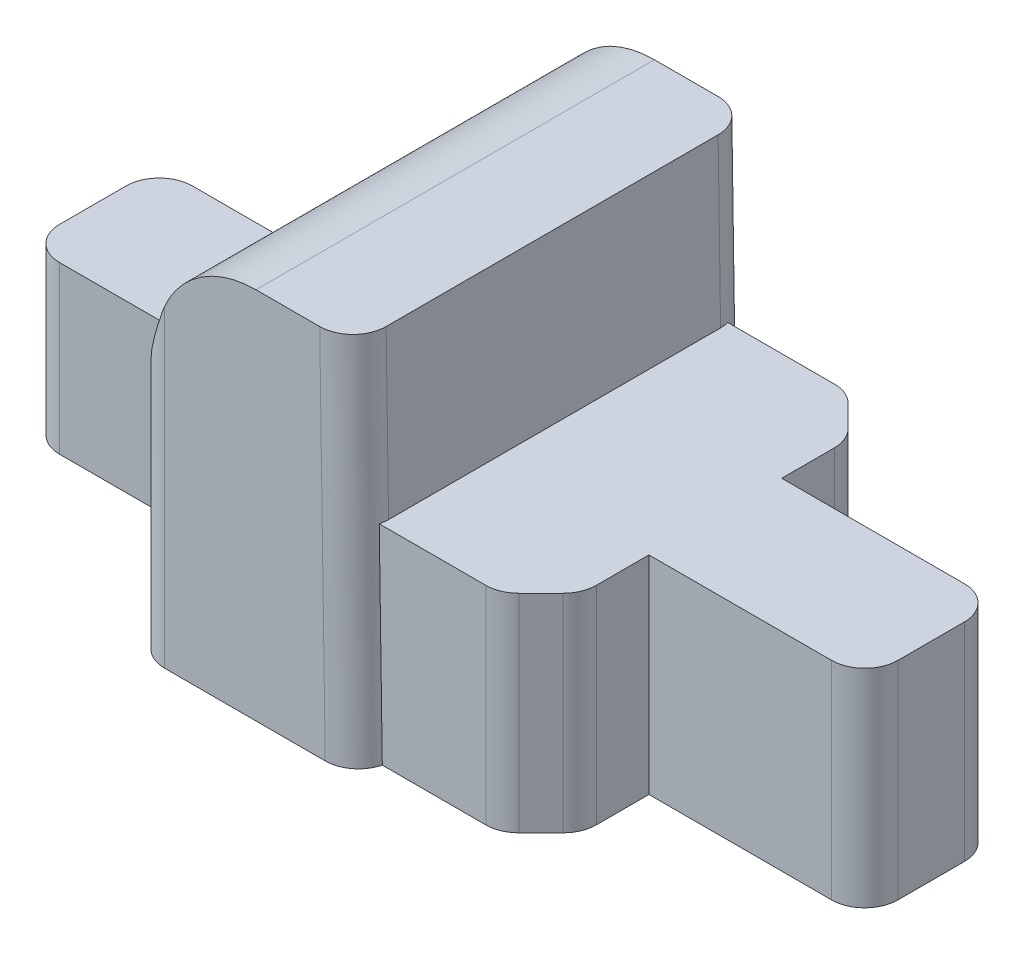
SolidWorks part; units mm, degrees
ref_plane "Front Plane" through (0, 0, 0) normal (0, 0, 1) x (1, 0, 0)
ref_plane "Top Plane" through (0, 0, 0) normal (0, 1, 0) x (1, 0, 0)
ref_plane "Right Plane" through (0, 0, 0) normal (1, 0, 0) x (0, 0, -1)
ref_plane "Plane1" through (0, 0, 203.2) normal (0, 0, 1) x (1, 0, 0)
sketch "Sketch2" plane through (0, 0, 203.2) normal (0, 0, 1) x (1, 0, 0)
  line L0 (0, 0) -> (-660.4, 0)
  line L1 (-660.4, 0) -> (-660.4, 508)
  line L2 (-660.4, 508) -> (0, 508)
  line L3 (0, 508) -> (0, 0)
  dimension "D1" = 660.4
  dimension "D2" = 508
ref_plane "Plane2" through (0, 0, 609.6) normal (0, 0, 1) x (1, 0, 0)
sketch "Sketch3" plane through (0, 0, 609.6) normal (0, 0, 1) x (1, 0, 0)
  line L1 (0, 0) -> (0, 508)
  line L2 (0, 0) -> (762, 0)
  line L3 (762, 0) -> (745.0612, 1143)
  line L4 (237.0612, 1143) -> (745.0612, 1143)
  line L5 (0, 508) -> (237.0612, 1143)
  dimension "D1" = 762
  dimension "D2" = 1143
  dimension "D3" = 508
ref_plane "Plane3" through (0, 0, 533.4) normal (0, 0, 1) x (1, 0, 0)
sketch "Sketch4" plane through (0, 0, 533.4) normal (0, 0, 1) x (1, 0, 0)
  line L1 (1244.6, 635) -> (752.5896, 635)
  line L2 (762, 0) -> (1244.6, 0)
  line L3 (1244.6, 0) -> (1244.6, 635)
  line L4 (762, 0) -> (745.0612, 1143) construction
  line L5 (752.5896, 635) -> (762, 0)
  dimension "D1" = 482.6
  dimension "D2" = 635
ref_plane "Plane4" through (0, 0, 203.2) normal (0, 0, 1) x (1, 0, 0)
sketch "Sketch5" plane through (0, 0, 203.2) normal (0, 0, 1) x (1, 0, 0)
  line L0 (1244.6, 0) -> (1244.6, 635) construction
  line L1 (1244.6, 0) -> (1244.6, 635)
  line L2 (1244.6, 0) -> (1905, 0)
  line L3 (1244.6, 635) -> (1905, 635)
  line L4 (1905, 635) -> (1905, 0)
  dimension "D1" = 660.4
extrude "Boss-Extrude1" add sketch "Sketch2" against normal blind 406.4
extrude "Boss-Extrude2" add sketch "Sketch3" against normal blind 1219.2
extrude "Boss-Extrude3" add sketch "Sketch4" against normal blind 1066.8
extrude "Boss-Extrude4" add sketch "Sketch5" against normal blind 406.4
fillet "Fillet2" radius 101.6 2 edges at (-660.4, 254, -203.2) (-660.4, 254, 203.2)
fillet "Fillet3" radius 101.6 2 edges at (1905, 317.5, -203.2) (1905, 317.5, 203.2)
chamfer "Chamfer1" distance 127 angle 45 2 edges at (1244.6, 317.5, -533.4) (1244.6, 317.5, 533.4)
fillet "Fillet4" radius 101.6 4 edges at (1244.6, 317.5, 406.4) (1117.6, 317.5, 533.4) (1244.6, 317.5, -406.4) (1117.6, 317.5, -533.4)
chamfer "Chamfer3" distance 127 angle 45 2 edges at (0, 254, -609.6) (0, 254, 609.6)
fillet "Fillet5" radius 101.6 6 edges at (753.5306, 571.5, 609.6) (753.5306, 571.5, -609.6) (127, 424.0932, -609.6) (0, 254, -482.6) (127, 424.0932, 609.6) (0, 254, 482.6)
fillet "Fillet6" radius 304.8 1 edges at (237.0612, 1143, 0)
sketch "Sketch10" plane through (0, 0, 609.6) normal (0, 0, 1) x (1, 0, 0)
  line L0 (0, 508) -> (313.9896, 1337.6045) construction
  line L1 (745.0612, 1143) -> (-64.3912, 1143) construction
  line L2 (745.0612, 1143) -> (443.8571, 1143)
  line L3 (168.2937, 952.6555) -> (0, 508)
  arc A0 (443.8571, 1143) -> (168.2937, 952.6555) centre (443.8571, 848.36) ccw
  point P9 (240.3355, 1143)
  dimension "D1" = 294.64
sketch "Sketch11" plane through (0, 0, 0) normal (0, -1, 0) x (1, 0, 0)
  line L18 (1075.5159, 533.4) -> (758.7734, 533.4)
  line L19 (660.3888, 609.6) -> (169.0841, 609.6)
  line L20 (97.242, 579.842) -> (29.758, 512.358)
  line L21 (0, 440.5159) -> (0, 203.2)
  line L22 (0, 203.2) -> (-558.8, 203.2)
  line L23 (-660.4, 101.6) -> (-660.4, -101.6)
  line L24 (-558.8, -203.2) -> (0, -203.2)
  line L25 (0, -203.2) -> (0, -440.5159)
  line L26 (29.758, -512.358) -> (97.242, -579.842)
  line L27 (169.0841, -609.6) -> (660.3888, -609.6)
  line L28 (758.7734, -533.4) -> (1075.5159, -533.4)
  line L29 (1147.358, -503.642) -> (1214.842, -436.158)
  line L30 (1244.6, -364.3159) -> (1244.6, -203.2)
  line L31 (1244.6, -203.2) -> (1803.4, -203.2)
  line L32 (1905, -101.6) -> (1905, 101.6)
  line L33 (1803.4, 203.2) -> (1244.6, 203.2)
  line L34 (1244.6, 203.2) -> (1244.6, 364.3159)
  line L35 (1214.842, 436.158) -> (1147.358, 503.642)
  line L36 (1075.5159, 533.4) -> (758.7734, 533.4)
  line L37 (660.3888, 609.6) -> (169.0841, 609.6)
  line L38 (97.242, 579.842) -> (29.758, 512.358)
  line L39 (0, 440.5159) -> (0, 203.2)
  line L40 (0, 203.2) -> (-558.8, 203.2)
  line L41 (-660.4, 101.6) -> (-660.4, -101.6)
  line L42 (-558.8, -203.2) -> (0, -203.2)
  line L43 (0, -203.2) -> (0, -440.5159)
  line L44 (29.758, -512.358) -> (97.242, -579.842)
  line L45 (169.0841, -609.6) -> (660.3888, -609.6)
  line L46 (758.7734, -533.4) -> (1075.5159, -533.4)
  line L47 (1147.358, -503.642) -> (1214.842, -436.158)
  line L48 (1244.6, -364.3159) -> (1244.6, -203.2)
  line L49 (1244.6, -203.2) -> (1803.4, -203.2)
  line L50 (1905, -101.6) -> (1905, 101.6)
  line L51 (1803.4, 203.2) -> (1244.6, 203.2)
  line L52 (1244.6, 203.2) -> (1244.6, 364.3159)
  line L53 (1214.842, 436.158) -> (1147.358, 503.642)
  arc A12 (169.0841, 609.6) -> (97.242, 579.842) centre (169.0841, 508) ccw
  arc A13 (29.758, 512.358) -> (0, 440.5159) centre (101.6, 440.5159) ccw
  arc A14 (-558.8, 203.2) -> (-660.4, 101.6) centre (-558.8, 101.6) ccw
  arc A15 (-660.4, -101.6) -> (-558.8, -203.2) centre (-558.8, -101.6) ccw
  arc A16 (0, -440.5159) -> (29.758, -512.358) centre (101.6, -440.5159) ccw
  arc A17 (97.242, -579.842) -> (169.0841, -609.6) centre (169.0841, -508) ccw
  arc A18 (1075.5159, -533.4) -> (1147.358, -503.642) centre (1075.5159, -431.8) ccw
  arc A19 (1214.842, -436.158) -> (1244.6, -364.3159) centre (1143, -364.3159) ccw
  arc A20 (1803.4, -203.2) -> (1905, -101.6) centre (1803.4, -101.6) ccw
  arc A21 (1905, 101.6) -> (1803.4, 203.2) centre (1803.4, 101.6) ccw
  arc A22 (1244.6, 364.3159) -> (1214.842, 436.158) centre (1143, 364.3159) ccw
  arc A23 (1147.358, 503.642) -> (1075.5159, 533.4) centre (1075.5159, 431.8) ccw
  arc A24 (169.0841, 609.6) -> (97.242, 579.842) centre (169.0841, 508) ccw
  arc A25 (29.758, 512.358) -> (0, 440.5159) centre (101.6, 440.5159) ccw
  arc A26 (-558.8, 203.2) -> (-660.4, 101.6) centre (-558.8, 101.6) ccw
  arc A27 (-660.4, -101.6) -> (-558.8, -203.2) centre (-558.8, -101.6) ccw
  arc A28 (0, -440.5159) -> (29.758, -512.358) centre (101.6, -440.5159) ccw
  arc A29 (97.242, -579.842) -> (169.0841, -609.6) centre (169.0841, -508) ccw
  arc A30 (1075.5159, -533.4) -> (1147.358, -503.642) centre (1075.5159, -431.8) ccw
  arc A31 (1214.842, -436.158) -> (1244.6, -364.3159) centre (1143, -364.3159) ccw
  arc A32 (1803.4, -203.2) -> (1905, -101.6) centre (1803.4, -101.6) ccw
  arc A33 (1905, 101.6) -> (1803.4, 203.2) centre (1803.4, 101.6) ccw
  arc A34 (1244.6, 364.3159) -> (1214.842, 436.158) centre (1143, 364.3159) ccw
  arc A35 (1147.358, 503.642) -> (1075.5159, 533.4) centre (1075.5159, 431.8) ccw
  ellipse E2 centre (660.3888, 508) end of major axis (762, 508) minor radius 101.6 (758.7734, 533.4) -> (660.3888, 609.6) ccw
  ellipse E3 centre (660.3888, -508) end of major axis (558.7777, -508) minor radius 101.6 (660.3888, -609.6) -> (758.7734, -533.4) ccw
  ellipse E4 centre (660.3888, 508) end of major axis (762, 508) minor radius 101.6 (758.7734, 533.4) -> (660.3888, 609.6) ccw
  ellipse E5 centre (660.3888, -508) end of major axis (558.7777, -508) minor radius 101.6 (660.3888, -609.6) -> (758.7734, -533.4) ccw
  dimension "D1" = 0
sketch "Sketch12" plane through (0, 0, 609.6) normal (0, 0, 1) x (1, 0, 0)
  line L4 (643.4501, 1143) -> (448.6195, 1143)
  line L5 (169.0841, 959.7032) -> (169.0841, 0)
  line L6 (169.0841, 0) -> (660.3888, 0)
  line L7 (660.3888, 0) -> (643.4501, 1143)
  line L8 (643.4501, 1143) -> (448.6195, 1143)
  line L9 (169.0841, 959.7032) -> (169.0841, 0)
  line L10 (169.0841, 0) -> (660.3888, 0)
  line L11 (660.3888, 0) -> (643.4501, 1143)
  arc A1 (448.6195, 1143) -> (169.0841, 959.7032) centre (448.6195, 838.2) ccw
  arc A2 (448.6195, 1143) -> (169.0841, 959.7032) centre (448.6195, 838.2) ccw
  dimension "D1" = 0
sketch "Sketch13" plane through (0, 0, -609.6) normal (0, 0, -1) x (-1, 0, 0)
  line L4 (-169.0841, 0) -> (-169.0841, 959.7032)
  line L5 (-448.6195, 1143) -> (-643.4501, 1143)
  line L6 (-643.4501, 1143) -> (-660.3888, 0)
  line L7 (-660.3888, 0) -> (-169.0841, 0)
  line L8 (-169.0841, 0) -> (-169.0841, 959.7032)
  line L9 (-448.6195, 1143) -> (-643.4501, 1143)
  line L10 (-643.4501, 1143) -> (-660.3888, 0)
  line L11 (-660.3888, 0) -> (-169.0841, 0)
  arc A1 (-169.0841, 959.7032) -> (-448.6195, 1143) centre (-448.6195, 838.2) ccw
  arc A2 (-169.0841, 959.7032) -> (-448.6195, 1143) centre (-448.6195, 838.2) ccw
  dimension "D1" = 0
sketch "Sketch14" plane through (0, 0, 203.2) normal (0, 0, 1) x (1, 0, 0)
  line L4 (0, 508) -> (-558.8, 508)
  line L5 (-558.8, 508) -> (-558.8, 0)
  line L6 (-558.8, 0) -> (0, 0)
  line L7 (0, 0) -> (0, 508)
  line L8 (0, 508) -> (-558.8, 508)
  line L9 (-558.8, 508) -> (-558.8, 0)
  line L10 (-558.8, 0) -> (0, 0)
  line L11 (0, 0) -> (0, 508)
  dimension "D1" = 0
sketch "Sketch15" plane through (0, 0, 203.2) normal (0, 0, 1) x (1, 0, 0)
  line L4 (1244.6, 0) -> (1803.4, 0)
  line L5 (1803.4, 0) -> (1803.4, 635)
  line L6 (1803.4, 635) -> (1244.6, 635)
  line L7 (1244.6, 635) -> (1244.6, 0)
  line L8 (1244.6, 0) -> (1803.4, 0)
  line L9 (1803.4, 0) -> (1803.4, 635)
  line L10 (1803.4, 635) -> (1244.6, 635)
  line L11 (1244.6, 635) -> (1244.6, 0)
  dimension "D1" = 0
sketch "Sketch16" plane through (0, 0, -203.2) normal (0, 0, -1) x (-1, 0, 0)
  line L4 (0, 0) -> (558.8, 0)
  line L5 (558.8, 0) -> (558.8, 508)
  line L6 (558.8, 508) -> (0, 508)
  line L7 (0, 508) -> (0, 0)
  line L8 (0, 0) -> (558.8, 0)
  line L9 (558.8, 0) -> (558.8, 508)
  line L10 (558.8, 508) -> (0, 508)
  line L11 (0, 508) -> (0, 0)
  dimension "D1" = 0
sketch "Sketch17" plane through (0, 0, -203.2) normal (0, 0, -1) x (-1, 0, 0)
  line L4 (-1244.6, 635) -> (-1803.4, 635)
  line L5 (-1803.4, 635) -> (-1803.4, 0)
  line L6 (-1803.4, 0) -> (-1244.6, 0)
  line L7 (-1244.6, 0) -> (-1244.6, 635)
  line L8 (-1244.6, 635) -> (-1803.4, 635)
  line L9 (-1803.4, 635) -> (-1803.4, 0)
  line L10 (-1803.4, 0) -> (-1244.6, 0)
  line L11 (-1244.6, 0) -> (-1244.6, 635)
  dimension "D1" = 0
sketch "Sketch18" plane through (0, 0, 533.4) normal (0, 0, 1) x (1, 0, 0)
  line L4 (758.7734, 0) -> (1075.5159, 0)
  line L5 (1075.5159, 0) -> (1075.5159, 635)
  line L6 (1075.5159, 635) -> (749.363, 635)
  line L7 (749.363, 635) -> (758.7734, 0)
  line L8 (758.7734, 0) -> (1075.5159, 0)
  line L9 (1075.5159, 0) -> (1075.5159, 635)
  line L10 (1075.5159, 635) -> (749.363, 635)
  line L11 (749.363, 635) -> (758.7734, 0)
  dimension "D1" = 0
sketch "Sketch20" plane through (-166.4505, 62.1401, 0) normal (-0.9368, 0.3497, 0) x (0, 0, 1)
  line L6 (609.4218, 942.1661) -> (-609.4218, 942.1661)
  line L7 (-579.842, 753.9521) -> (-512.358, 561.001)
  line L8 (-440.5159, 475.9168) -> (-203.2, 475.9168)
  line L9 (-203.2, 475.9168) -> (203.2, 475.9168)
  line L10 (203.2, 475.9168) -> (440.5159, 475.9168)
  line L11 (512.358, 561.001) -> (579.842, 753.9521)
  line L12 (609.4218, 942.1661) -> (-609.4218, 942.1661)
  line L13 (-579.842, 753.9521) -> (-512.358, 561.001)
  line L14 (-440.5159, 475.9168) -> (-203.2, 475.9168)
  line L15 (-203.2, 475.9168) -> (203.2, 475.9168)
  line L16 (203.2, 475.9168) -> (440.5159, 475.9168)
  line L17 (512.358, 561.001) -> (579.842, 753.9521)
  ellipse E4 centre (508, 959.3635) end of major axis (508, 1249.8591) minor radius 101.6 (579.842, 753.9521) -> (609.4218, 942.1661) ccw
  ellipse E5 centre (-508, 959.3635) end of major axis (-508, 668.8679) minor radius 101.6 (-609.4218, 942.1661) -> (-579.842, 753.9521) ccw
  ellipse E6 centre (-440.5159, 766.4124) end of major axis (-440.5159, 1056.908) minor radius 101.6 (-512.358, 561.001) -> (-440.5159, 475.9168) ccw
  ellipse E7 centre (440.5159, 766.4124) end of major axis (440.5159, 1056.908) minor radius 101.6 (440.5159, 475.9168) -> (512.358, 561.001) ccw
  ellipse E8 centre (508, 959.3635) end of major axis (508, 1249.8591) minor radius 101.6 (579.842, 753.9521) -> (609.4218, 942.1661) ccw
  ellipse E9 centre (-508, 959.3635) end of major axis (-508, 668.8679) minor radius 101.6 (-609.4218, 942.1661) -> (-579.842, 753.9521) ccw
  ellipse E10 centre (-440.5159, 766.4124) end of major axis (-440.5159, 1056.908) minor radius 101.6 (-512.358, 561.001) -> (-440.5159, 475.9168) ccw
  ellipse E11 centre (440.5159, 766.4124) end of major axis (440.5159, 1056.908) minor radius 101.6 (440.5159, 475.9168) -> (512.358, 561.001) ccw
  dimension "D1" = 0
sketch "Sketch21" plane through (-660.4, 0, 0) normal (-1, 0, 0) x (0, 0, 1)
  line L4 (101.6, 508) -> (-101.6, 508)
  line L5 (-101.6, 508) -> (-101.6, 0)
  line L6 (-101.6, 0) -> (101.6, 0)
  line L7 (101.6, 0) -> (101.6, 508)
  line L8 (101.6, 508) -> (-101.6, 508)
  line L9 (-101.6, 508) -> (-101.6, 0)
  line L10 (-101.6, 0) -> (101.6, 0)
  line L11 (101.6, 0) -> (101.6, 508)
  dimension "D1" = 0
sketch "Sketch22" plane through (1905, 0, 0) normal (1, 0, 0) x (0, 0, -1)
  line L4 (-101.6, 0) -> (101.6, 0)
  line L5 (101.6, 0) -> (101.6, 635)
  line L6 (101.6, 635) -> (-101.6, 635)
  line L7 (-101.6, 635) -> (-101.6, 0)
  line L8 (-101.6, 0) -> (101.6, 0)
  line L9 (101.6, 0) -> (101.6, 635)
  line L10 (101.6, 635) -> (-101.6, 635)
  line L11 (-101.6, 635) -> (-101.6, 0)
  dimension "D1" = 0
sketch "Sketch23" plane through (761.8327, 11.29, 0) normal (0.9999, 0.0148, 0) x (0, 0, -1)
  line L4 (508, 1131.8342) -> (-508, 1131.8342)
  line L5 (-508, 1131.8342) -> (-508, 623.7785)
  line L6 (-508, 623.7785) -> (508, 623.7785)
  line L7 (508, 623.7785) -> (508, 1131.8342)
  line L8 (508, 1131.8342) -> (-508, 1131.8342)
  line L9 (-508, 1131.8342) -> (-508, 623.7785)
  line L10 (-508, 623.7785) -> (508, 623.7785)
  line L11 (508, 623.7785) -> (508, 1131.8342)
  dimension "D1" = 0
sketch3d "3DSketch2"
  line L0 (0, 508, -440.5159) -> (0, 508, 440.5159)
  line L1 (29.758, 587.7106, 512.358) -> (163.0694, 944.8029, 609.4218)
  line L2 (448.6195, 1143, 609.6) -> (643.4501, 1143, 609.6)
  line L3 (643.4501, 1143, 609.6) -> (745.068, 1142.5435, 508)
  line L4 (745.0612, 1143, 508) -> (752.5896, 635, 508) construction
